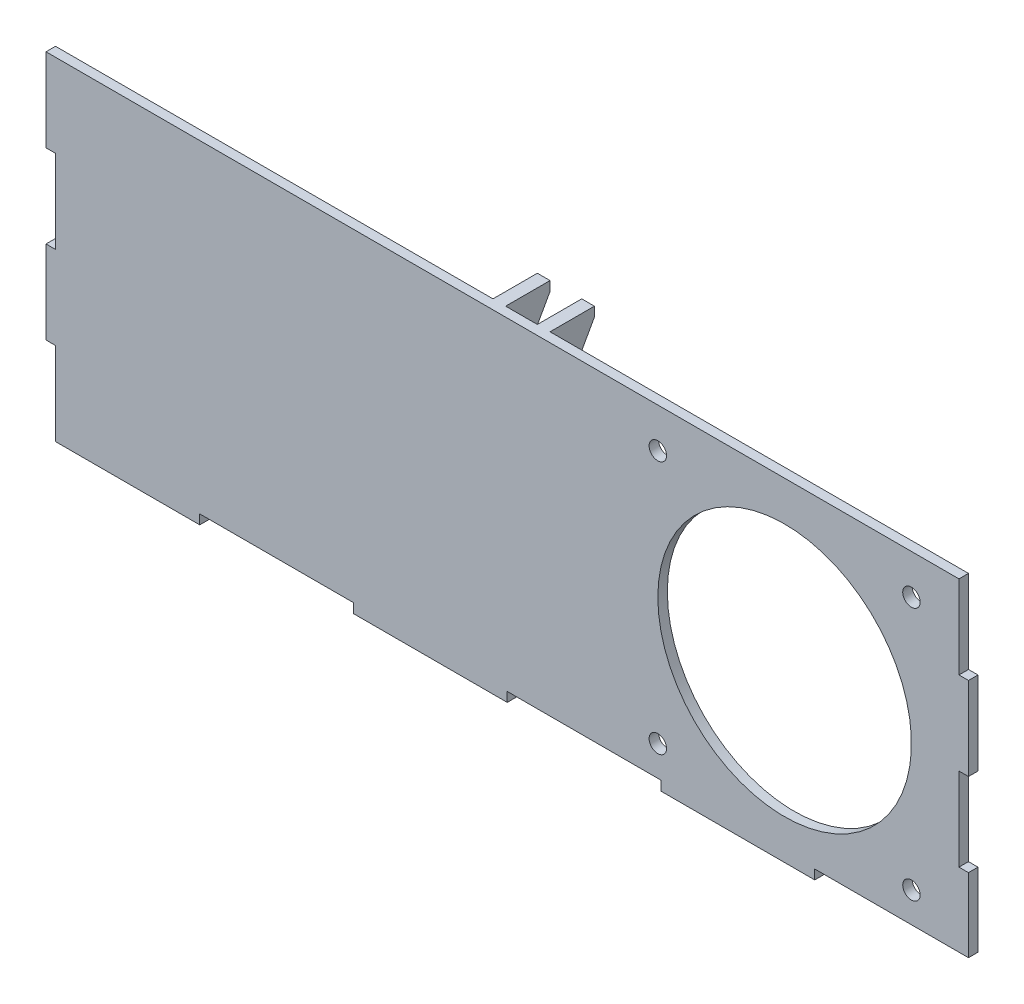
SolidWorks part; units mm, degrees
ref_plane "Спереди" through (0, 0, 0) normal (0, 0, 1) x (1, 0, 0)
ref_plane "Сверху" through (0, 0, 0) normal (0, 1, 0) x (1, 0, 0)
ref_plane "Справа" through (0, 0, 0) normal (1, 0, 0) x (0, 0, -1)
other "Configuration Table"
sketch "Эскиз1" plane through (0, 0, 0) normal (0, 0, 1) x (1, 0, 0)
  line L1 (-145.5, -52.5) -> (145.5, -52.5)
  line L2 (-145.5, -52.5) -> (-145.5, 52.5)
  line L3 (-145.5, 52.5) -> (145.5, 52.5)
  line L4 (145.5, -52.5) -> (145.5, 52.5)
  line L5 (-145.5, -52.5) -> (145.5, 52.5) construction
  line L6 (-145.5, 52.5) -> (145.5, -52.5) construction
  point P0 (0, 0)
  dimension "D1" = 291
  dimension "D2" = 105
extrude "Бобышка-Вытянуть1" add sketch "Эскиз1" along normal blind 3
sketch "Эскиз2" plane through (0, 0, 3) normal (0, 0, 1) x (1, 0, 0)
  line L0 (-145.5, 52.5) -> (-145.5, -52.5) construction
  line L3 (-145.5, -26.25) -> (-142.5, -26.25)
  line L5 (-145.5, 0) -> (-142.5, 0)
  line L6 (-145.5, 0) -> (-145.5, 26.25)
  line L7 (-145.5, 26.25) -> (-142.5, 26.25)
  line L8 (-142.5, 0) -> (-142.5, 26.25)
  line L9 (-145.5, -52.5) -> (145.5, -52.5) construction
  line L13 (-97, -52.5) -> (-97, -49.5)
  line L15 (-48.5, -52.5) -> (-48.5, -49.5)
  line L17 (0, -52.5) -> (0, -49.5)
  line L18 (145.5, -52.5) -> (145.5, 52.5) construction
  line L20 (48.5, -52.5) -> (48.5, -49.5)
  line L22 (97, -52.5) -> (97, -49.5)
  line L23 (145.5, 52.5) -> (142.5, 52.5)
  line L24 (145.5, 52.5) -> (145.5, 26.25)
  line L25 (145.5, 26.25) -> (142.5, 26.25)
  line L26 (142.5, 52.5) -> (142.5, 26.25)
  line L27 (145.5, 0) -> (142.5, 0)
  line L28 (145.5, 0) -> (145.5, -26.25)
  line L29 (145.5, -26.25) -> (142.5, -26.25)
  line L30 (142.5, 0) -> (142.5, -26.25)
  line L31 (145.5, 52.5) -> (-145.5, 52.5) construction
  line L32 (97, -49.5) -> (145.5, -49.5)
  line L33 (145.5, -49.5) -> (145.5, -52.5)
  line L34 (145.5, -52.5) -> (97, -52.5)
  line L35 (48.5, -49.5) -> (0, -49.5)
  line L36 (48.5, -52.5) -> (0, -52.5)
  line L37 (-48.5, -49.5) -> (-97, -49.5)
  line L38 (-48.5, -52.5) -> (-97, -52.5)
  line L39 (-142.5, -26.25) -> (-142.5, -52.5)
  line L40 (-142.5, -52.5) -> (-145.5, -52.5)
  line L41 (-145.5, -52.5) -> (-145.5, -26.25)
  dimension "D1" = 26.25
  dimension "D2" = 26.25
  dimension "D3" = 3
  dimension "D4" = 3
  dimension "D5" = 48.5
  dimension "D6" = 48.5
  dimension "D7" = 48.5
  dimension "D8" = 48.5
  dimension "D9" = 26.25
  dimension "D10" = 26.25
  dimension "D11" = 26.25
  dimension "D12" = 3
  dimension "D13" = 3
  dimension "D14" = 48.5
  dimension "D15" = 26.25
extrude "Вырез-Вытянуть1" cut sketch "Эскиз2" against normal up to surface (3 mm away) up to face at (0, 0, 0)
sketch "Эскиз3" plane through (0, 0, 0) normal (0, 0, -1) x (-1, 0, 0)
  line L0 (-142.5, 52.5) -> (-142.5, 26.25) construction
  line L1 (-137.5, -44.5) -> (137.5, -44.5) construction
  line L2 (-137.5, -44.5) -> (-137.5, 44.5) construction
  line L3 (-137.5, 44.5) -> (137.5, 44.5) construction
  line L4 (137.5, -44.5) -> (137.5, 44.5) construction
  line L5 (-137.5, -44.5) -> (137.5, 44.5) construction
  line L6 (-137.5, 44.5) -> (137.5, -44.5) construction
  line L9 (-48.5, -49.5) -> (0, -49.5) construction
  line L10 (-127.5, -40) -> (-47.5, -40) construction
  line L11 (-127.5, -40) -> (-127.5, 40) construction
  line L12 (-127.5, 40) -> (-47.5, 40) construction
  line L13 (-47.5, -40) -> (-47.5, 40) construction
  line L14 (-127.5, -40) -> (-47.5, 40) construction
  line L15 (-127.5, 40) -> (-47.5, -40) construction
  circle A0 centre (-87.5, 0) radius 40
  circle A1 centre (-127.5, 40) radius 2.75
  circle A2 centre (-47.5, 40) radius 2.75
  circle A3 centre (-47.5, -40) radius 2.75
  circle A4 centre (-127.5, -40) radius 2.75
  point P0 (0, 0)
  dimension "D3" = 80
  dimension "D5" = 5.5
  dimension "D1" = 5
  dimension "D2" = 5
  dimension "D4" = 87.5
extrude "Вырез-Вытянуть2" cut sketch "Эскиз3" against normal up to surface (3 mm away) up to face at (0, -19.5, 3)
sketch "Эскиз4" plane through (0, 0, 0) normal (0, 0, -1) x (-1, 0, 0)
  line L0 (-142.5, 52.5) -> (145.5, 52.5) construction
  line L1 (3.5, 52.5) -> (7.5, 52.5)
  line L2 (3.5, 52.5) -> (3.5, 24.5)
  line L3 (3.5, 24.5) -> (7.5, 24.5)
  line L4 (7.5, 52.5) -> (7.5, 24.5)
  line L6 (-6.5, 52.5) -> (-10.5, 52.5)
  line L7 (-6.5, 52.5) -> (-6.5, 24.5)
  line L8 (-6.5, 24.5) -> (-10.5, 24.5)
  line L9 (-10.5, 52.5) -> (-10.5, 24.5)
  line L10 (-145.5, 0) -> (-145.5, 26.25) construction
  dimension "D1" = 135
  dimension "D2" = 4
  dimension "D3" = 10
  dimension "D4" = 4
  dimension "D5" = 28
  dimension "D6" = 28
extrude "Бобышка-Вытянуть2" add sketch "Эскиз4" along normal blind 14
sketch "Эскиз5" plane through (10.5, 0, 0) normal (1, 0, 0) x (0, 0, -1)
  line L0 (0, 24.5) -> (14, 24.5)
  line L1 (14, 24.5) -> (14, 49.5)
  line L2 (14, 52.5) -> (14, 24.5) construction
  line L3 (14, 49.5) -> (0, 24.5)
  dimension "D1" = 25
extrude "Вырез-Вытянуть3" cut sketch "Эскиз5" against normal up to surface (18 mm away) up to face at (-7.5, 38.5, -7)
